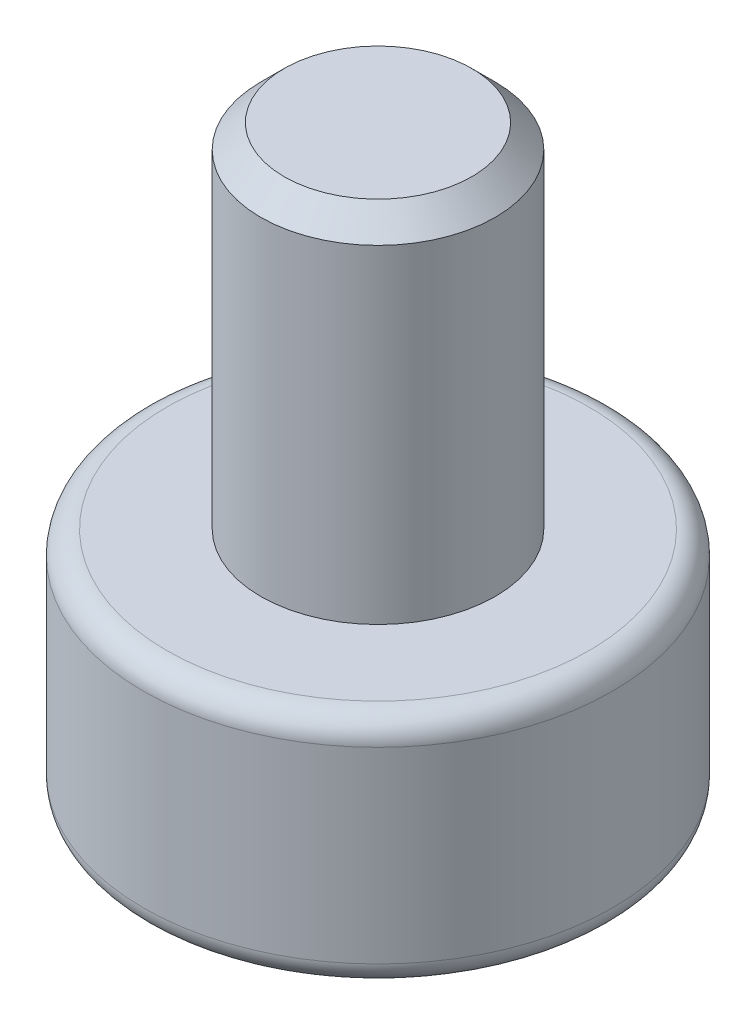
SolidWorks part; units mm, degrees
material "AISI 304"
ref_plane "前视基准面" through (0, 0, 0) normal (0, 0, 1) x (1, 0, 0)
ref_plane "上视基准面" through (0, 0, 0) normal (0, 1, 0) x (1, 0, 0)
ref_plane "右视基准面" through (0, 0, 0) normal (1, 0, 0) x (0, 0, -1)
sketch "草图2" plane through (0, 0, 0) normal (0, 1, 0) x (1, 0, 0)
  circle A0 centre (0, 0) radius 2
  dimension "D1" = 4
extrude "凸台-拉伸1" add sketch "草图2" along normal blind 2
sketch "草图3" plane through (0, 2, 0) normal (0, 1, 0) x (1, 0, 0)
  circle A0 centre (0, 0) radius 1
  dimension "D1" = 2
extrude "凸台-拉伸2" add sketch "草图3" along normal blind 3
fillet "圆角1" radius 0.2 2 edges at (0, 2, 2) (0, 0, 2)
sketch "草图4" plane through (0, 0, 0) normal (0, -1, 0) x (1, 0, 0)
  circle A0 centre (0, 0) radius 0.765
  dimension "D1" = 1.53
extrude "切除-拉伸1" cut sketch "草图4" against normal blind 1.52
chamfer "倒角1" distance 0.1 angle 45 1 edges at (0, 0, -0.765)
chamfer "倒角2" distance 0.2 angle 45 1 edges at (0, 5, 1)
